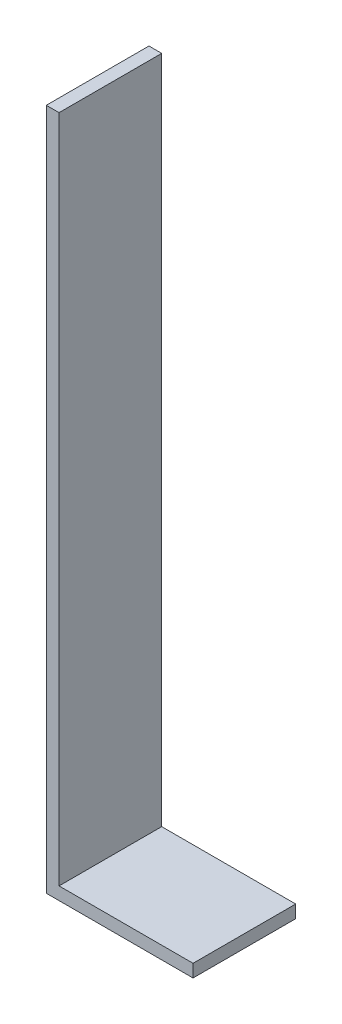
SolidWorks part; units mm, degrees
ref_plane "Alzado" through (0, 0, 0) normal (0, 0, 1) x (1, 0, 0)
ref_plane "Planta" through (0, 0, 0) normal (0, 1, 0) x (1, 0, 0)
ref_plane "Vista lateral" through (0, 0, 0) normal (1, 0, 0) x (0, 0, -1)
sketch "Croquis1" plane through (0, 0, 0) normal (0, 0, 1) x (1, 0, 0)
  line L0 (0, 0) -> (72.62, 0)
  line L1 (0, 0) -> (0, 337.71)
  line L2 (6.31, 6.31) -> (72.62, 6.31)
  line L3 (6.31, 6.31) -> (6.31, 337.71)
  line L4 (72.62, 6.31) -> (72.62, 0)
  line L5 (6.31, 337.71) -> (0, 337.71)
  dimension "D1" = 72.62
  dimension "D2" = 337.71
  dimension "D3" = 6.31
extrude "Saliente-Extruir1" add sketch "Croquis1" along normal blind 50.8
